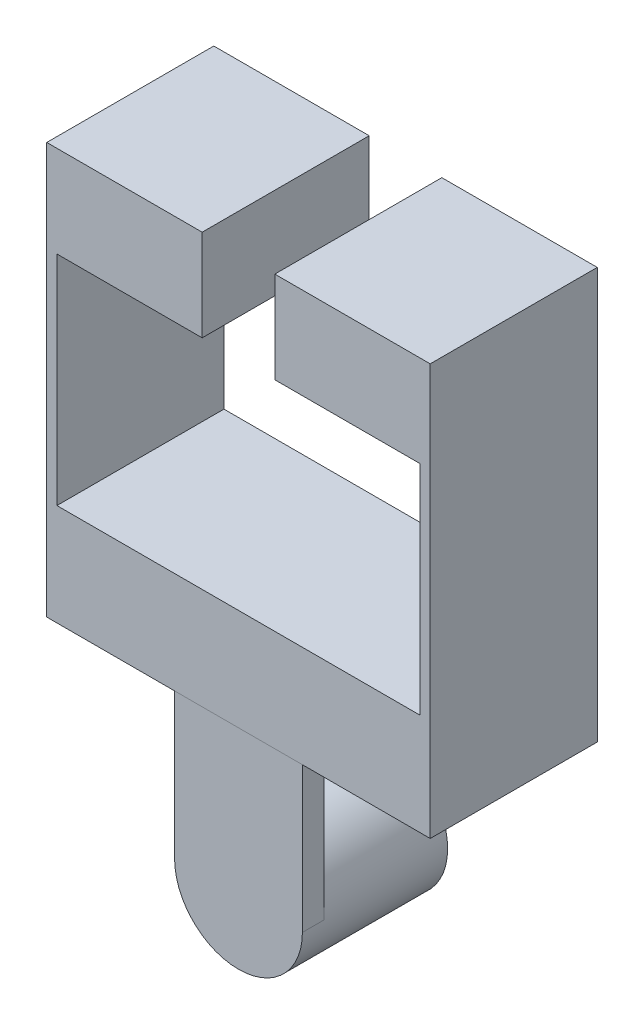
SolidWorks part; units mm, degrees
material "ASTM A36 Steel"
ref_plane "Front Plane" through (0, 0, 0) normal (0, 0, 1) x (1, 0, 0)
ref_plane "Top Plane" through (0, 0, 0) normal (0, 1, 0) x (1, 0, 0)
ref_plane "Right Plane" through (0, 0, 0) normal (1, 0, 0) x (0, 0, -1)
sketch "Sketch1" plane through (0, 0, 0) normal (0, 0, 1) x (1, 0, 0)
  line L0 (-12.0433, 53.9479) -> (15.1347, 53.9479)
  line L1 (15.1347, 53.9479) -> (15.1347, -17.9341)
  line L3 (-51.9213, -17.9341) -> (-51.9213, 53.9479)
  line L4 (-51.9213, 53.9479) -> (-24.7433, 53.9479)
  line L5 (-24.7433, 53.9479) -> (-24.7433, 37.9459)
  line L6 (-24.7433, 37.9459) -> (-50.1433, 37.9459)
  line L7 (-50.1433, 37.9459) -> (-50.1433, -0.1541)
  line L8 (-50.1433, -0.1541) -> (13.3567, -0.1541)
  line L9 (13.3567, -0.1541) -> (13.3567, 37.9459)
  line L10 (13.3567, 37.9459) -> (-12.0433, 37.9459)
  line L11 (-12.0433, 37.9459) -> (-12.0433, 53.9479)
  line L16 (-18.3933, -17.9341) -> (-18.3933, 53.9479) construction
  line L17 (-51.9213, -17.9341) -> (15.1347, -17.9341)
  dimension "D2" = 67.056
  dimension "D5" = 63.5
  dimension "D6" = 38.1
  dimension "D7" = 38.1
  dimension "D8" = 1.778
  dimension "D9" = 1.778
  dimension "D10" = 16.002
  dimension "D11" = 16.002
  dimension "D12" = 25.4
  dimension "D13" = 25.4
extrude "Boss-Extrude2" add sketch "Sketch1" along normal blind 29.21 contours L17 L1 L0 L11 L10 L9 L8 L7 L6 L5 L4 L3
sketch "Sketch2" plane through (0, 0, 29.21) normal (0, 0, 1) x (1, 0, 0)
  line L0 (-18.3933, -17.9341) -> (-18.3933, 54.2273) construction
  line L1 (-51.9213, -17.9341) -> (15.1347, -17.9341) construction
  line L2 (-29.5693, -17.9341) -> (-29.5693, -43.3341)
  line L3 (-29.5693, -43.3341) -> (-7.2173, -43.3341)
  line L4 (-7.2173, -43.3341) -> (-7.2173, -17.9341)
  line L5 (-7.2173, -17.9341) -> (-29.5693, -17.9341)
  line L6 (-18.3933, -17.9341) -> (-18.3933, -43.3341) construction
  dimension "D1" = 25.4
  dimension "D2" = 22.352
extrude "Boss-Extrude3" add sketch "Sketch2" against normal blind 3.81
sketch "Sketch5" plane through (0, 0, 29.21) normal (0, 0, 1) x (1, 0, 0)
  line L0 (-29.5693, -43.3341) -> (-7.2173, -43.3341) construction
  circle A0 centre (-18.3933, -43.3341) radius 11.176
  dimension "D1" = 22.352
extrude "Boss-Extrude6" add sketch "Sketch5" against normal blind 25.4
sketch "Sketch6" plane through (0, 0, 29.21) normal (0, 0, 1) x (1, 0, 0)
  line L0 (-51.9213, -17.9341) -> (15.1347, -17.9341)
split line "Split Line1"
equation "\"F\"= 600'force"
equation "\"Sy\"= 36259.43'yield strength"
equation "\"SF\"= 4'safety factor"
equation "\"E\"= 29007547.53'elastic modulus"
equation "\"Def\"= .005'deflection"
equation "\"A length\"= 1"
equation "\"b length\"= 1"
equation "\"c length\"= 2.5"
equation "\"c width\"= 1"
equation "\"d width\"= 1"
equation "\"d height\"= 1.5"
equation "\"e width\"= 1"
equation "\"e length\"= .9990"
equation "\"Za\"= \"SF\" * 2 * \"F\" * \"A length\" / ( 2 * \"Sy\" )"
equation "\"a radius\"= ( 4 * \"Za\" / PI ) ^ ( 1 / 3 )"
equation "\"a diameter\"= 2 * \"a radius\""
equation "\"b width\"= \"a diameter\""
equation "\"b stress\"= \"Sy\" / \"SF\""
equation "\"b area\"= ( 2 * \"F\" ) / \"b stress\""
equation "\"b thickness\"= \"b area\" / \"b width\""
equation "\"c stress\"= \"Sy\" / \"SF\""
equation "\"c moment\"= ( 2 * \"F\" ) * \"c length\" / 4"
equation "\"Zc\"= \"c moment\" / \"c stress\""
equation "\"c height\"= ( 6 * \"Zc\" / \"c width\" ) ^ ( 1 / 2 )"
equation "\"d stress\"= \"Sy\" / \"SF\""
equation "\"d area\"= \"F\" / \"d stress\""
equation "\"d length\"= \"d area\" / \"d width\""
equation "\"e stress\"= \"Sy\" / \"SF\""
equation "\"e moment\"= \"F\" * \"e length\""
equation "\"e height\"= ( 6 * \"e moment\" / ( \"e width\" * \"e stress\" ) ) ^ ( 1 / 2 )"
